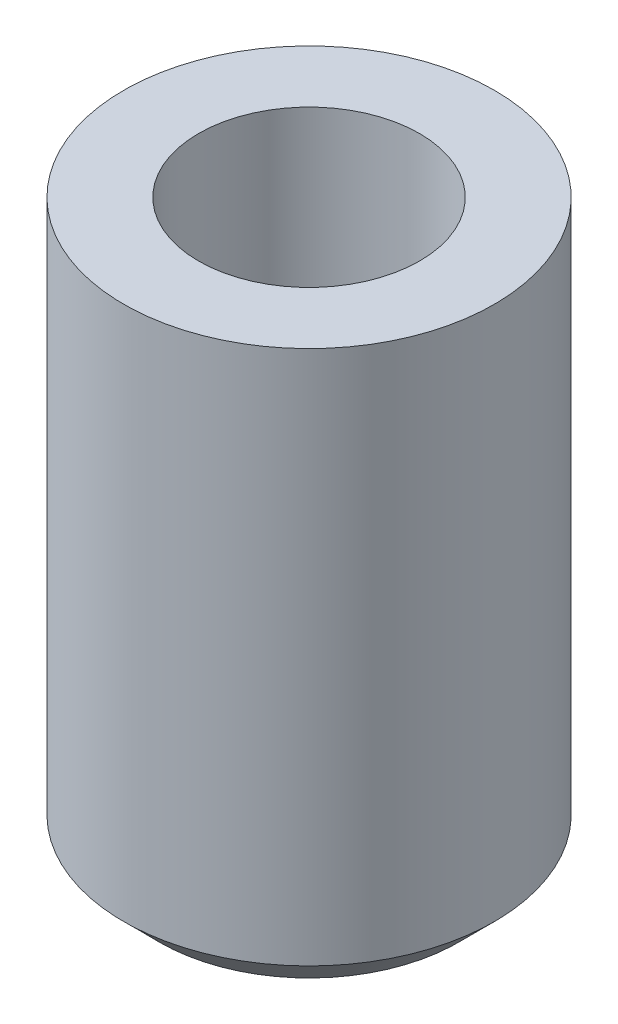
SolidWorks part; units mm, degrees
ref_plane "Front Plane" through (0, 0, 0) normal (0, 0, 1) x (1, 0, 0)
ref_plane "Top Plane" through (0, 0, 0) normal (0, 1, 0) x (1, 0, 0)
ref_plane "Right Plane" through (0, 0, 0) normal (1, 0, 0) x (0, 0, -1)
sketch "Sketch2" plane through (0, 0, 0) normal (1, 0, 0) x (0, 0, -1)
  line L0 (0, 0) -> (2.6, 0)
  line L1 (2.6, 0) -> (2.6, 8)
  line L2 (2.6, 8) -> (1.55, 8)
  line L3 (1.55, 8) -> (1.55, 2)
  line L4 (1.55, 2) -> (0, 2)
  line L5 (0, 0) -> (0, 8.7656) construction
  line L6 (0, 2) -> (0, 0)
  dimension "D1" = 2.6
  dimension "D2" = 1.55
  dimension "D3" = 6
  dimension "D4" = 2
revolve "Revolve1" add sketch "Sketch2" angle 360 about L5
chamfer "Chamfer1" distance 0.5 angle 45 1 edges at (0, 0, -2.6)
